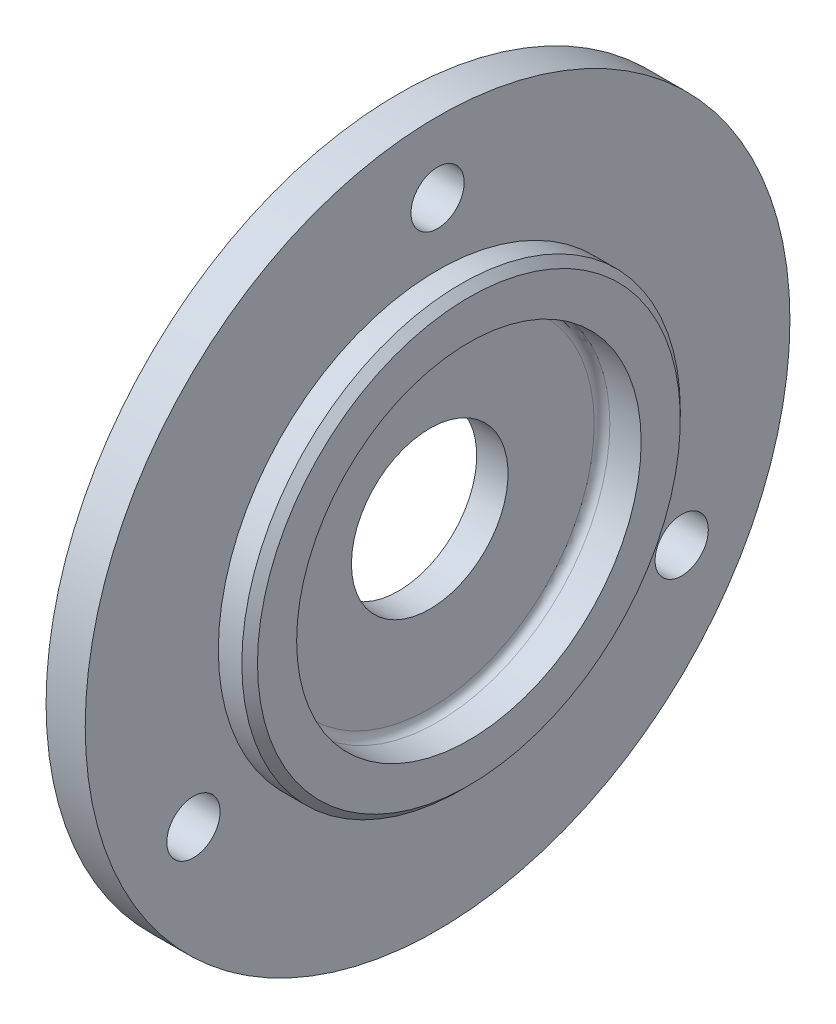
SolidWorks part; units mm, degrees
material "Alliage 1060"
ref_plane "Plan de face" through (0, 0, 0) normal (0, 0, 1) x (1, 0, 0)
ref_plane "Plan de dessus" through (0, 0, 0) normal (0, 1, 0) x (1, 0, 0)
ref_plane "Plan de droite" through (0, 0, 0) normal (1, 0, 0) x (0, 0, -1)
sketch "Esquisse1" plane through (0, 0, 0) normal (0, 0, 1) x (1, 0, 0)
  line L0 (-14.7778, 0) -> (22.3469, 0) construction
  line L1 (-0.5, 5) -> (-0.5, 10.5)
  line L2 (0, 11) -> (2, 11)
  line L3 (2, 11) -> (2, 13.5)
  line L4 (1.5, 14) -> (0, 14)
  line L5 (0, 14) -> (0, 22.5)
  line L6 (0, 22.5) -> (-2.5, 22.5)
  line L7 (-2.5, 22.5) -> (-2.5, 5)
  line L8 (-2.5, 5) -> (-0.5, 5)
  line L9 (2, 13.5) -> (1.5, 14)
  arc A0 (-0.5, 10.5) -> (0, 11) centre (0, 10.5) cw
  point P7 (2, 14)
  dimension "D8" = 0.5
  dimension "D1" = 10
  dimension "D2" = 28
  dimension "D3" = 22
  dimension "D4" = 45
  dimension "D5" = 2.5
  dimension "D6" = 2
  dimension "D7" = 2
  dimension "D11" = 0.5
revolve "Révolution1" add sketch "Esquisse1" angle 360 about L0
sketch "Esquisse2" plane through (0, 0, 0) normal (1, 0, 0) x (0, 0, -1)
  circle A0 centre (0, 18) radius 1.7
  circle A1 centre (15.5885, -9) radius 1.7
  circle A2 centre (-15.5885, -9) radius 1.7
  dimension "D1" = 3.4
  dimension "D2" = 18
extrude "Enlèv. mat.-Extru.1" cut sketch "Esquisse2" against normal blind 10
